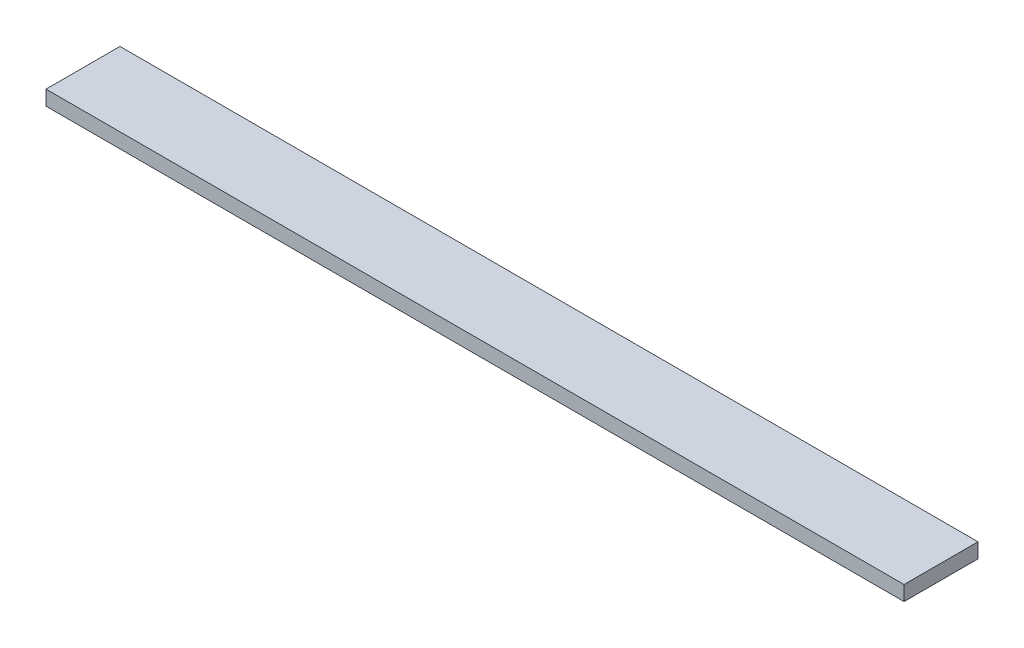
SolidWorks part; units mm, degrees
ref_plane "Front Plane" through (0, 0, 0) normal (0, 0, 1) x (1, 0, 0)
ref_plane "Top Plane" through (0, 0, 0) normal (0, 1, 0) x (1, 0, 0)
ref_plane "Right Plane" through (0, 0, 0) normal (1, 0, 0) x (0, 0, -1)
sketch "Sketch1" plane through (0, 0, 0) normal (0, 1, 0) x (1, 0, 0)
  line L1 (-147.32, -12.7) -> (147.32, -12.7)
  line L2 (-147.32, -12.7) -> (-147.32, 12.7)
  line L3 (-147.32, 12.7) -> (147.32, 12.7)
  line L4 (147.32, -12.7) -> (147.32, 12.7)
  line L5 (-147.32, -12.7) -> (147.32, 12.7) construction
  line L6 (-147.32, 12.7) -> (147.32, -12.7) construction
  point P0 (0, 0)
  dimension "D1" = 294.64
  dimension "D2" = 25.4
extrude "Boss-Extrude1" add sketch "Sketch1" along normal blind 5.08
